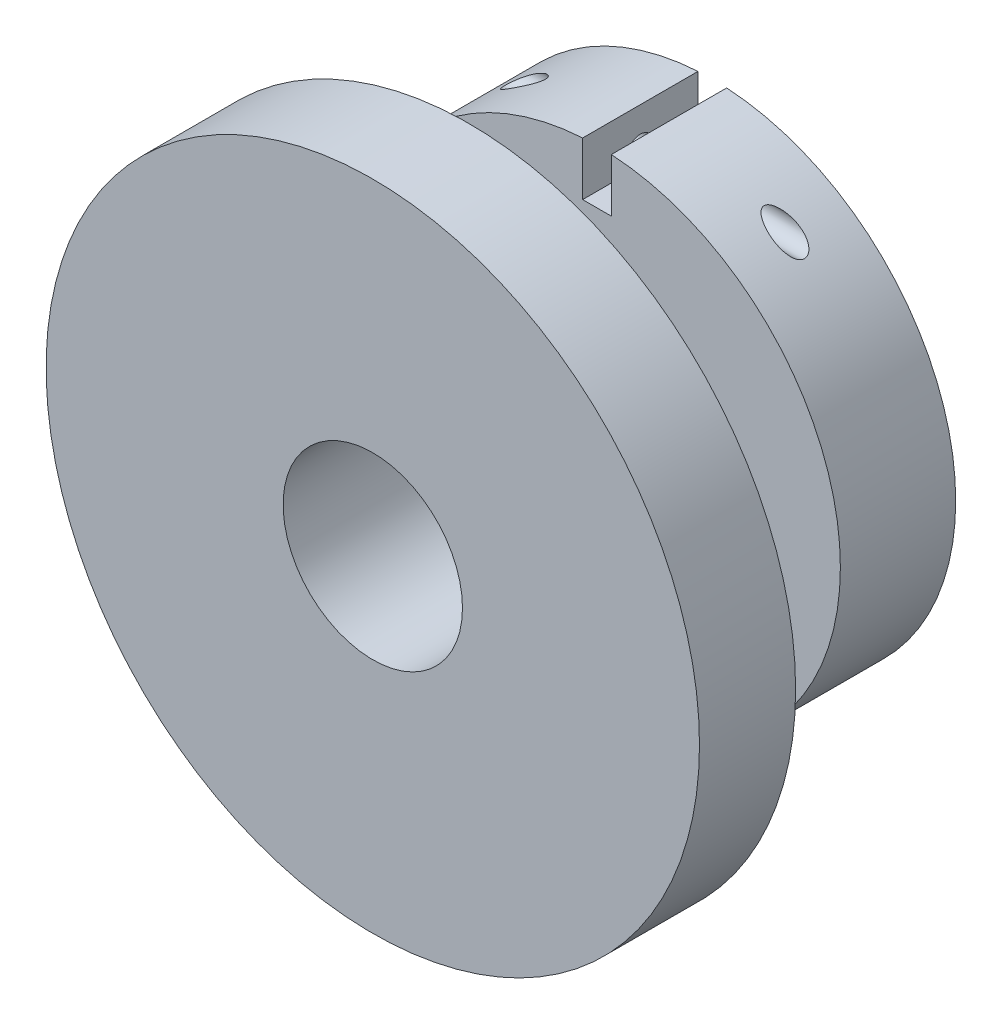
SolidWorks part; units mm, degrees
ref_plane "Plan de face" through (0, 0, 0) normal (0, 0, 1) x (1, 0, 0)
ref_plane "Plan de dessus" through (0, 0, 0) normal (0, 1, 0) x (1, 0, 0)
ref_plane "Plan de droite" through (0, 0, 0) normal (1, 0, 0) x (0, 0, -1)
sketch "Esquisse1" plane through (0, 0, 0) normal (0, 0, 1) x (1, 0, 0)
  circle A0 centre (0, 0) radius 50
  circle A1 centre (0, 0) radius 67.85
  dimension "D1" = 100
  dimension "D2" = 135.7
extrude "Boss.-Extru.1" add sketch "Esquisse1" against normal blind 71.4
sketch "Esquisse3" plane through (0, 0, -71.4) normal (0, 0, -1) x (-1, 0, 0)
  circle A0 centre (0, 0) radius 50
  circle A1 centre (0, 0) radius 135.7
  dimension "D1" = 100
  dimension "D2" = 271.4
extrude "Boss.-Extru.2" add sketch "Esquisse3" along normal blind 64.3
sketch "Esquisse6" plane through (0, 0, -135.7) normal (0, 0, -1) x (-1, 0, 0)
  line L0 (0, 0) -> (0, 157.3265) construction
  line L1 (-8, 105.7) -> (8, 105.7)
  line L2 (-8, 105.7) -> (-8, 135.464)
  line L3 (8, 105.7) -> (8, 135.464)
  line L4 (74.635, 0) -> (-74.635, 0) construction
  line L5 (8, -105.7) -> (8, -135.464)
  line L6 (-8, -105.7) -> (8, -105.7)
  line L7 (-8, -105.7) -> (-8, -135.464)
  arc A0 (8, -135.464) -> (-8, -135.464) centre (0, 0) cw
  arc A1 (8, 135.464) -> (-8, 135.464) centre (0, 0) ccw
  point P5 (0, 105.7)
  point P6 (0, 135.7)
  dimension "D2" = 271.4
  dimension "D1" = 16
  dimension "D3" = 30
extrude "Enlèv. mat.-Extru.2" cut sketch "Esquisse6" against normal through all
sketch "Esquisse7" plane through (0, 0, 0) normal (1, 0, 0) x (0, 0, -1)
  line L0 (103.55, 135.464) -> (103.55, 114.064) construction
  line L1 (71.4, 135.464) -> (135.7, 135.464) construction
  line L2 (74.635, 0) -> (-74.635, 0) construction
  circle A0 centre (103.55, 114.064) radius 7.15
  circle A1 centre (103.55, -114.064) radius 7.15
  dimension "D2" = 14.3
  dimension "D1" = 21.4
extrude "Enlèv. mat.-Extru.3" cut sketch "Esquisse7" against normal through all and the other way through all
sketch "Esquisse8" plane through (0, 0, 0) normal (0, 0, 1) x (1, 0, 0)
  circle A0 centre (0, 0) radius 50
  circle A1 centre (0, 0) radius 182.15
  dimension "D1" = 364.3
extrude "Boss.-Extru.3" add sketch "Esquisse8" along normal blind 53.6
